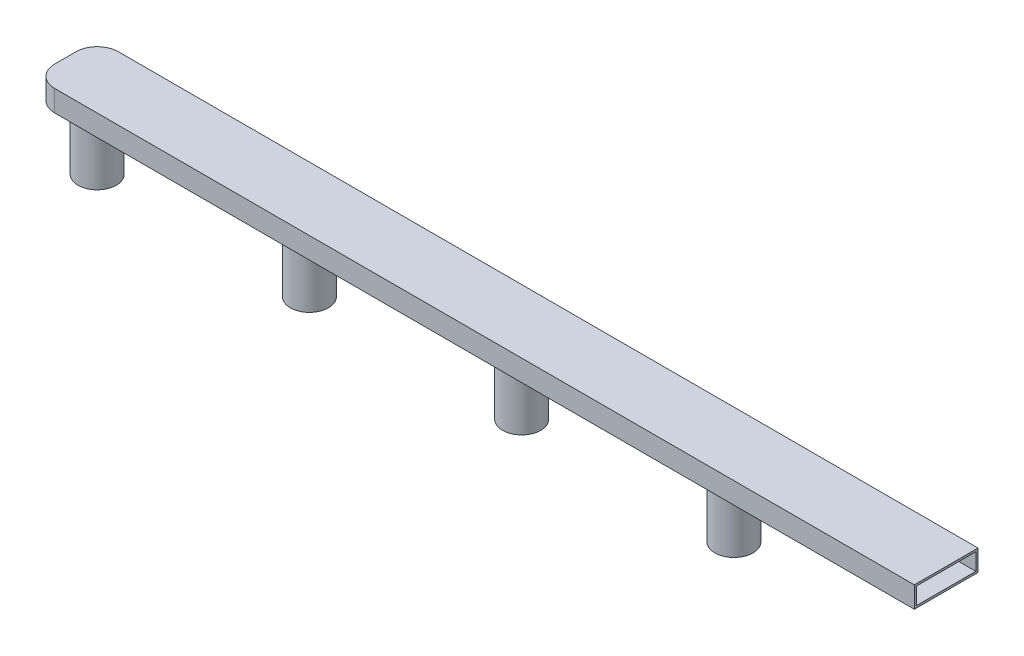
SolidWorks part; units mm, degrees
material "Cast Alloy Steel"
ref_plane "Front Plane" through (0, 0, 0) normal (0, 0, 1) x (1, 0, 0)
ref_plane "Top Plane" through (0, 0, 0) normal (0, 1, 0) x (1, 0, 0)
ref_plane "Right Plane" through (0, 0, 0) normal (1, 0, 0) x (0, 0, -1)
sketch "Sketch1" plane through (0, 0, 0) normal (0, 1, 0) x (1, 0, 0)
  circle A0 centre (-150, 0) radius 6.5
  circle A1 centre (-50, 0) radius 6.5
  circle A2 centre (50, 0) radius 6.5
  circle A3 centre (150, 0) radius 6.5
  circle A4 centre (-150, 0) radius 9
  circle A5 centre (-50, 0) radius 9
  circle A6 centre (50, 0) radius 9
  circle A7 centre (150, 0) radius 9
  dimension "D1" = 13
  dimension "D6" = 18
  dimension "D2" = 50
  dimension "D3" = 100
  dimension "D4" = 100
  dimension "D5" = 50
extrude "Boss-Extrude1" add sketch "Sketch1" against normal blind 30
sketch "Sketch2" plane through (0, 0, 0) normal (0, 1, 0) x (1, 0, 0)
  line L1 (-155, 15) -> (250, 15)
  line L2 (-165, 5) -> (-165, -5)
  line L3 (-155, -15) -> (250, -15)
  line L4 (250, 15) -> (250, -15)
  circle A0 centre (150, 0) radius 9 construction
  circle A1 centre (-150, 0) radius 9 construction
  arc A4 (-165, -5) -> (-155, -15) centre (-155, -5) ccw
  arc A5 (-155, 15) -> (-165, 5) centre (-155, 5) ccw
  point P1 (-165, 0)
  point P3 (0, 0)
  point P4 (250, 0)
  point P11 (0, 0)
  point P12 (250, 15)
  point P15 (250, -15)
  dimension "D2" = 100
  dimension "D3" = 15
  dimension "D4" = 10
  dimension "D1" = 30
extrude "Boss-Extrude2" add sketch "Sketch2" along normal blind 10 separate body
shell "Shell3" thickness 1
